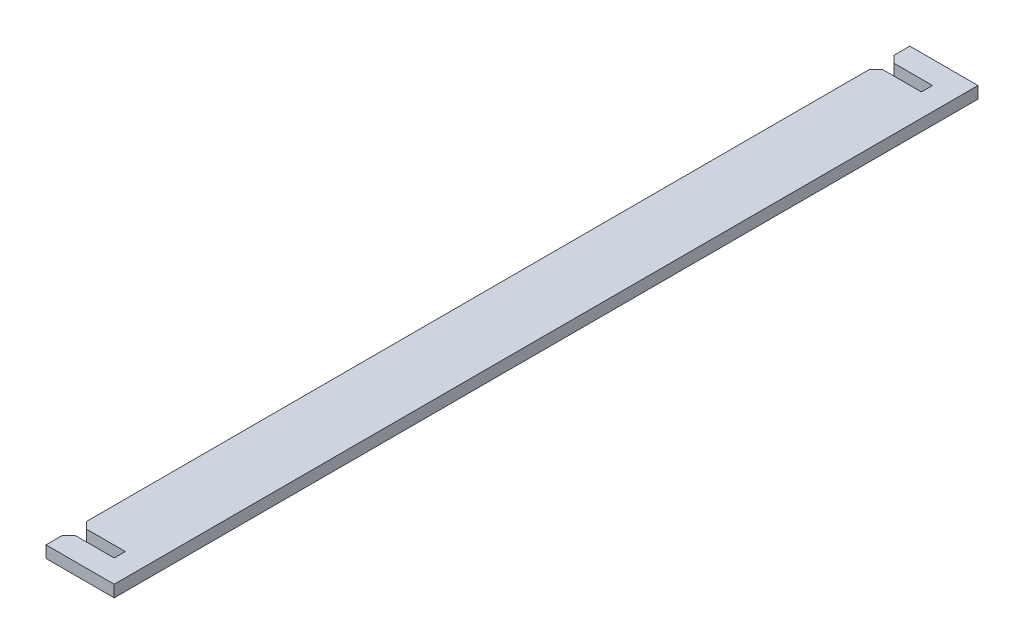
SolidWorks part; units mm, degrees
ref_plane "Front Plane" through (0, 0, 0) normal (0, 0, 1) x (1, 0, 0)
ref_plane "Top Plane" through (0, 0, 0) normal (0, 1, 0) x (1, 0, 0)
ref_plane "Right Plane" through (0, 0, 0) normal (1, 0, 0) x (0, 0, -1)
sketch "Sketch1" plane through (0, 0, 0) normal (0, 1, 0) x (1, 0, 0)
  line L1 (0, 0) -> (30, 0)
  line L2 (0, 0) -> (0, 380)
  line L3 (0, 380) -> (30, 380)
  line L4 (30, 0) -> (30, 380)
  dimension "D1" = 30
  dimension "D2" = 380
extrude "Boss-Extrude1" add sketch "Sketch1" along normal blind 5.2
sketch "Sketch2" plane through (0, 5.2, 0) normal (0, 1, 0) x (1, 0, 0)
  line L0 (0, 380) -> (0, 0) construction
  line L1 (0, 370) -> (20, 370)
  line L2 (0, 370) -> (0, 365.1)
  line L3 (0, 365.1) -> (20, 365.1)
  line L4 (20, 370) -> (20, 365.1)
  line L6 (0, 14.9) -> (20, 14.9)
  line L7 (0, 14.9) -> (0, 10)
  line L8 (0, 10) -> (20, 10)
  line L9 (20, 14.9) -> (20, 10)
  dimension "D1" = 4.9
  dimension "D2" = 20
  dimension "D3" = 10
  dimension "D4" = 10
extrude "Cut-Extrude1" cut sketch "Sketch2" against normal blind 10
chamfer "Chamfer1" distance 3 angle 45 4 edges at (0, 2.6, -10) (0, 2.6, -14.9) (0, 2.6, -365.1) (0, 2.6, -370)
equation "\"thick\"= 5.2'board thickness"
equation "\"fit\"= 0.3mm'fit adjustment"
equation "\"depth\"= \"thick\" * 1.5'cut depth"
equation "\"chamfer\"= \"thick\" / 2'fillet radius"
equation "\"width\"= \"thick\" - \"fit\"'cut width"
equation "\"gap\"= \"depth\" * 2'cut gap"
equation "\"curv\"= \"gap\" * 2'curvature radius"
equation "\"D1@Boss-Extrude1\"=\"thick\""
equation "\"D1@Sketch2\"=\"width\""
